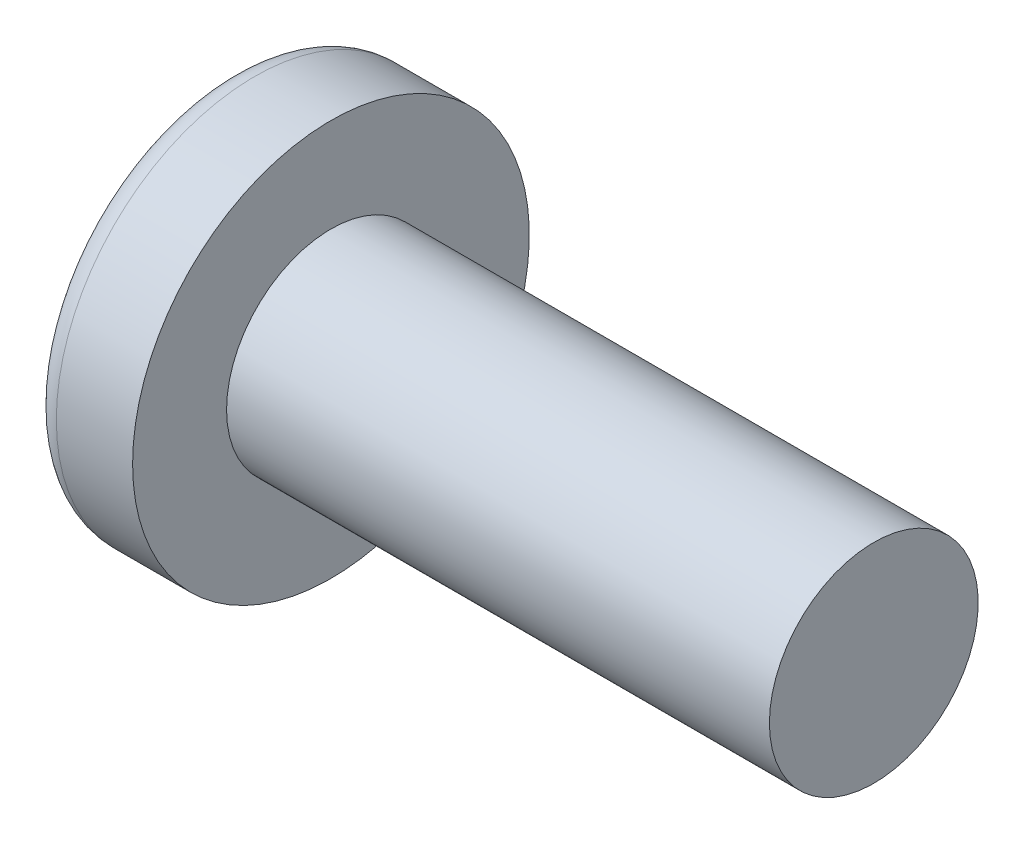
SolidWorks part; units mm, degrees
ref_plane "Plane1" through (0, 0, 0) normal (0, 0, 1) x (1, 0, 0)
ref_plane "Plane2" through (0, 0, 0) normal (0, 1, 0) x (1, 0, 0)
ref_plane "Plane3" through (0, 0, 0) normal (1, 0, 0) x (0, 0, -1)
sketch "BodySke" plane through (0, 0, 0) normal (0, 0, 1) x (1, 0, 0)
  line L0 (3.7, 2.5) -> (3.7, 4.75)
  line L1 (4.5, 6.35) -> (4.5, -3.175) construction
  line L2 (-25.4, 0) -> (127, 0) construction
  line L3 (16.7, 0) -> (0, 0)
  line L4 (3.7, 2.5) -> (16.7, 2.5)
  line L5 (16.7, 2.5) -> (16.7, 0)
  line L6 (1.8732, 4.75) -> (3.7, 4.75)
  line L7 (3.7, -2.5) -> (16.7, -2.5) construction
  line L8 (10.7, 6.35) -> (10.7, -3.175) construction
  arc A0 (1.3764, 4.4865) -> (0, 0) centre (8, 0) ccw
  arc A2 (1.3764, 4.4865) -> (1.8732, 4.75) centre (1.8732, 4.15) cw
  dimension "Head_crown_rad" = 8
  dimension "Head_fillet_rad" = 0.6
  dimension "Diameter" = 5
  dimension "Length" = 13
  dimension "Head_ht" = 3.7
  dimension "Head_dia" = 9.5
  dimension "Advance" = 0.8
revolve "Base-Revolve" add sketch "BodySke" angle 360 about L2
cosmetic thread "ThreadCosmetic" [suppressed] parameters "Thread_length"=12.2, "Thread_minor"=4.11
sketch "Sketch3" plane through (0, 0, 0) normal (1, 0, 0) x (0, 0, -1)
  line L0 (0.5, -2.45) -> (-0.5, -2.45)
  line L1 (0.5, -2.45) -> (0.5, 2.45)
  line L2 (-0.5, 2.45) -> (0.5, 2.45)
  line L3 (-0.5, 2.45) -> (-0.5, -2.45)
  dimension "Cross_dia" = 4.9
  dimension "D1" = 2.45
  dimension "Cross_width" = 1
  dimension "D2" = 0.5
ref_plane "Plane4" through (2.95, 0, 0) normal (1, 0, 0) x (0, 0, -1)
sketch "Sketch4" plane through (2.95, 0, 0) normal (1, 0, 0) x (0, 0, -1)
  line L0 (0.25, -0.25) -> (-0.25, -0.25)
  line L1 (0.25, -0.25) -> (0.25, 0.25)
  line L2 (-0.25, 0.25) -> (0.25, 0.25)
  line L3 (-0.25, 0.25) -> (-0.25, -0.25)
  dimension "D2" = 0.5
  dimension "D1" = 0.5
  dimension "D3" = 0.25
  dimension "D4" = 0.25
loft "Cut-Loft1" cut profiles "Sketch3", "Sketch4"
pattern_circular "CirPattern1" count 2 every 90 about axis through (0, 0, 0) along (1, 0, 0) of "Cut-Loft1"
sketch "ThdSchSke" plane through (0, 0, 0) normal (0, 0, 1) x (1, 0, 0)
  line L0 (10.7, -2.055) -> (10.3884, -2.5)
  line L1 (10.7, -2.055) -> (11.0116, -2.5)
  line L2 (11.0116, -2.5) -> (11.0116, -3.125)
  line L3 (-3.175, 0) -> (5.1513, 0) construction
  line L5 (11.0116, -3.125) -> (10.3884, -3.125)
  line L6 (10.3884, -3.125) -> (10.3884, -2.5)
  dimension "Diameter" = 5
  dimension "SideAngle" = 55
  dimension "VeeAngle" = 70
  dimension "Thread_minor" = 4.11
  dimension "Overcut" = 6.25
  dimension "Start" = 4.5
revolve "ThreadSchematic" [suppressed] cut sketch "ThdSchSke" angle 360 about L3
pattern_linear "ThdSchPat" [suppressed]
equation "\"D1@Sketch3\" = \"Cross_dia@Sketch3\" / 2"
equation "\"D2@Sketch3\" = \"Cross_width@Sketch3\" / 2"
equation "\"D1@Sketch4\" = \"Cross_width@Sketch3\" *.5"
equation "\"D2@Sketch4\" = \"D1@Sketch4\""
equation "\"D3@Sketch4\" = \"D1@Sketch4\" / 2"
equation "\"D4@Sketch4\" = \"D2@Sketch4\" / 2"
equation "\"Thread_length@ThreadCosmetic\" = ((sgn( (\"Length@BodySke\" - \"Advance@BodySke\" ) - \"Thread_nom@BodySke\" )-1)*( (\"Length@BodySke\" - \"Advance@BodySke\" ) - \"Thread_nom@BodySke\" ))/-2+ \"Thread_nom@BodySke\""
equation "\"Thread_minor@ThdSchSke\" = \"Thread_minor@ThreadCosmetic\""
equation "\"Diameter@ThdSchSke\" = \"Diameter@BodySke\""
equation "\"Overcut@ThdSchSke\" = \"Diameter@BodySke\" * 1.25"
equation "\"Start@ThdSchSke\" = \"Head_ht@BodySke\" + \"Length@BodySke\" - \"Thread_length@ThreadCosmetic\"  '---Non-countersunk---"
equation "\"Num_threads@ThdSchPat\" = int( \"Thread_length@ThreadCosmetic\" / \"Advance@BodySke\" + 0.999 )  + 1"
equation "\"Advance@ThdSchPat\" = \"Thread_length@ThreadCosmetic\" /  (\"Num_threads@ThdSchPat\" - 1) 'relax it"
